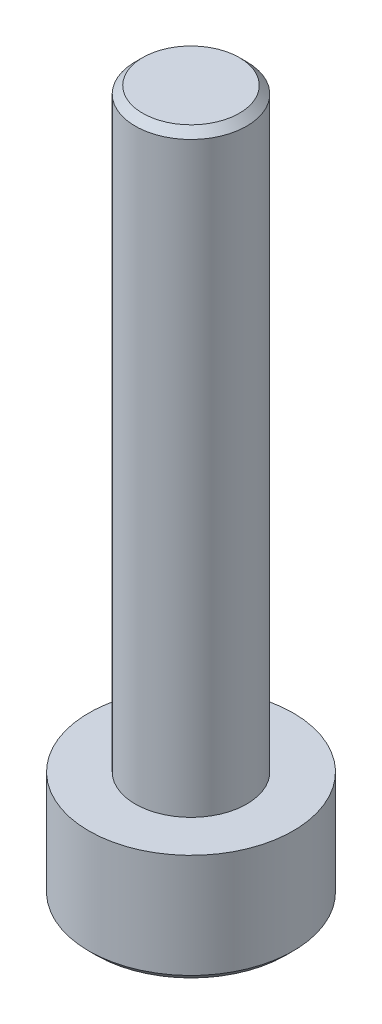
SolidWorks part; units mm, degrees
ref_plane "Front Plane" through (0, 0, 0) normal (0, 0, 1) x (1, 0, 0)
ref_plane "Top Plane" through (0, 0, 0) normal (0, 1, 0) x (1, 0, 0)
ref_plane "Right Plane" through (0, 0, 0) normal (1, 0, 0) x (0, 0, -1)
sketch "Reconstructed nominal axial profile" plane through (0, 0, 0) normal (0, 0, 1) x (1, 0, 0)
  line L0 (0, -500) -> (0, 50) construction
  line L1 (0, -3) -> (2.55, -3)
  line L2 (2.55, -3) -> (2.75, -2.8)
  line L3 (2.75, -2.8) -> (2.75, 0)
  line L4 (2.75, 0) -> (1.5, 0)
  line L5 (1.5, 0) -> (1.5, 15.8)
  line L6 (1.5, 15.8) -> (1.3, 16)
  line L7 (1.3, 16) -> (0, 16)
  line L8 (0, 16) -> (0, -3)
revolve "Native revolved geometry" add sketch "Reconstructed nominal axial profile" angle 360 about L0
sketch "Sketch2" plane through (0, 0, 0) normal (0, 1, 0) x (1, 0, 0)
  line L0 (1.4434, 0) -> (0.7217, -1.25)
  line L1 (0.7217, -1.25) -> (-0.7217, -1.25)
  line L2 (-0.7217, -1.25) -> (-1.4434, 0)
  line L3 (-1.4434, 0) -> (-0.7217, 1.25)
  line L4 (-0.7217, 1.25) -> (0.7217, 1.25)
  line L5 (0.7217, 1.25) -> (1.4434, 0)
extrude "Simplified nominal hex socket" cut sketch "Sketch2" along normal blind 1.5 from offset 3
